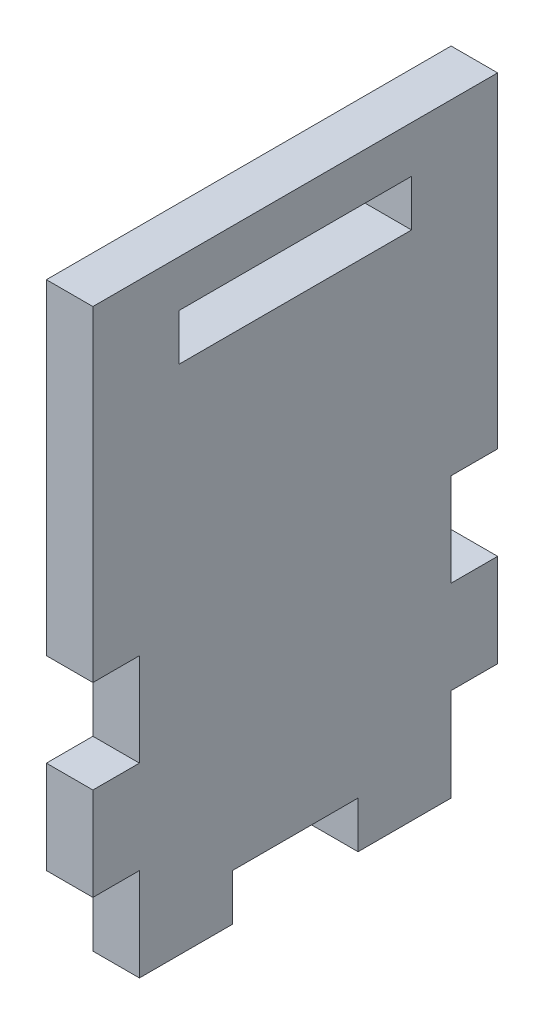
SolidWorks part; units mm, degrees
ref_plane "Plano frontal" through (0, 0, 0) normal (0, 0, 1) x (1, 0, 0)
ref_plane "Plano superior" through (0, 0, 0) normal (0, 1, 0) x (1, 0, 0)
ref_plane "Plano direito" through (0, 0, 0) normal (1, 0, 0) x (0, 0, -1)
sketch "ParedeEsboco" plane through (0, 0, 0) normal (1, 0, 0) x (0, 0, -1)
  line L0 (0, -19.5) -> (0, 19.5) construction
  line L6 (13.05, -13.5) -> (10.05, -13.5)
  line L7 (-7.5, 16.5) -> (7.5, 16.5)
  line L8 (-7.5, 16.5) -> (-7.5, 13.5)
  line L9 (-7.5, 13.5) -> (7.5, 13.5)
  line L10 (7.5, 16.5) -> (7.5, 13.5)
  line L11 (-13.05, 10.5) -> (13.05, 10.5) construction
  line L12 (-10.05, -19.5) -> (-10.05, -13.5)
  line L13 (-10.05, -13.5) -> (-13.05, -13.5)
  line L14 (-13.05, -13.5) -> (-13.05, -7.5)
  line L15 (-13.05, -7.5) -> (-10.05, -7.5)
  line L16 (-10.05, -7.5) -> (-10.05, -1.5)
  line L17 (-10.05, -1.5) -> (-13.05, -1.5)
  line L18 (-13.05, -1.5) -> (-13.05, 10.5)
  line L19 (-13.05, 10.5) -> (-13.05, 19.5)
  line L20 (13.05, 19.5) -> (13.05, 10.5)
  line L21 (13.05, 10.5) -> (13.05, -1.5)
  line L22 (13.05, -1.5) -> (10.05, -1.5)
  line L23 (10.05, -1.5) -> (10.05, -7.5)
  line L24 (10.05, -7.5) -> (13.05, -7.5)
  line L26 (-13.05, 19.5) -> (13.05, 19.5)
  line L27 (10.05, -13.5) -> (10.05, -19.5)
  line L28 (13.05, -13.5) -> (13.05, -7.5)
  line L29 (10.05, -19.5) -> (4.05, -19.5)
  line L30 (4.05, -19.5) -> (4.05, -16.5)
  line L31 (4.05, -16.5) -> (-4.05, -16.5)
  line L32 (-4.05, -16.5) -> (-4.05, -19.5)
  line L33 (-4.05, -19.5) -> (-10.05, -19.5)
  point P0 (0, 0)
  point P2 (0, 0)
  point P10 (0, 16.5)
  point P22 (0, 19.5)
  dimension "D1" = 26.1
  dimension "D2" = 39
  dimension "D3" = 3
  dimension "D4" = 3
  dimension "D5" = 15
  dimension "D6" = 3
  dimension "D7" = 6
  dimension "D8" = 6
  dimension "D9" = 6
  dimension "D10" = 9
  dimension "D11" = 3
  dimension "D12" = 6
  dimension "D13" = 6
  dimension "D14" = 6
  dimension "D15" = 6
  dimension "D16" = 3
extrude "Parede" add sketch "ParedeEsboco" along normal blind 3
